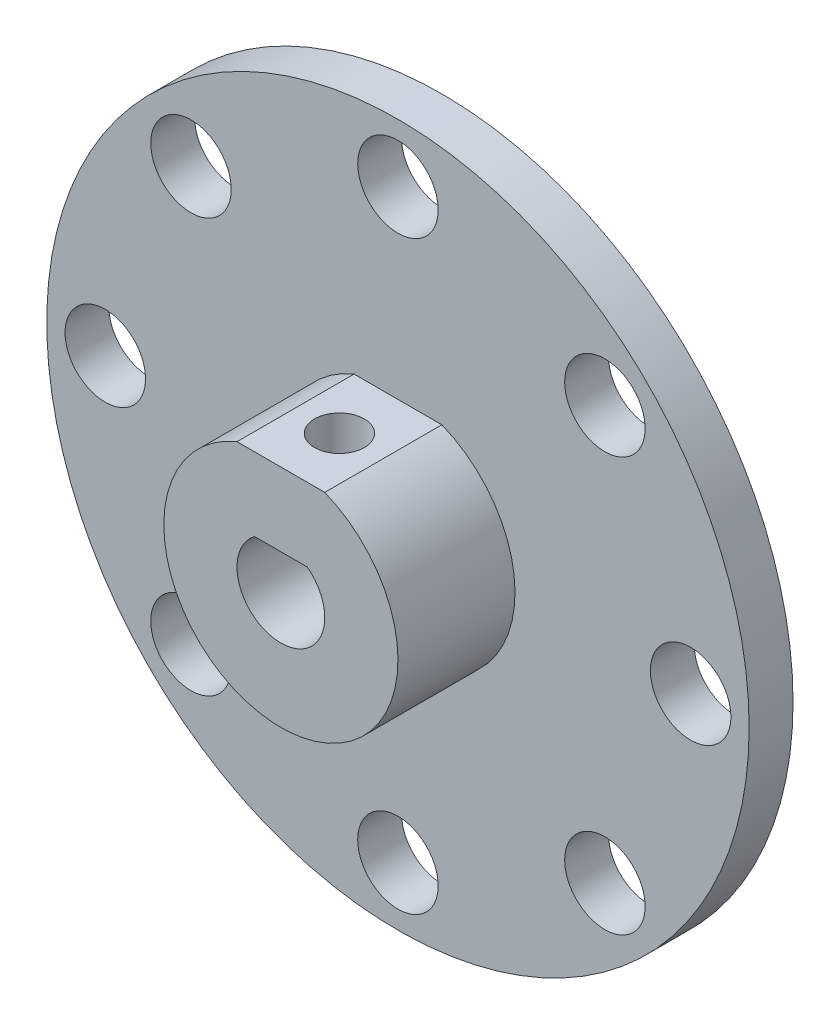
SolidWorks part; units mm, degrees
ref_plane "Alzado" through (0, 0, 0) normal (0, 0, 1) x (1, 0, 0)
ref_plane "Planta" through (0, 0, 0) normal (0, 1, 0) x (1, 0, 0)
ref_plane "Vista lateral" through (0, 0, 0) normal (1, 0, 0) x (0, 0, -1)
sketch "Croquis1" plane through (0, 0, 0) normal (1, 0, 0) x (0, 0, -1)
  line L0 (0, 16.8101) -> (0, -16.8101) construction
  line L1 (-25.6232, 0) -> (25.6232, 0) construction
  line L2 (-6.5, 0) -> (6.5, 0)
  line L3 (6.5, 0) -> (6.5, 9)
  line L4 (6.5, 9) -> (4.5, 9)
  line L5 (4.5, 9) -> (4.5, 24)
  line L6 (4.5, 24) -> (1.5, 24)
  line L7 (1.5, 24) -> (1.5, 8)
  line L8 (1.5, 8) -> (-6.5, 8)
  line L9 (-6.5, 8) -> (-6.5, 0)
  point P5 (0, 0)
  point P8 (0, 0)
  dimension "D1" = 9
  dimension "D2" = 24
  dimension "D3" = 2
  dimension "D4" = 13
  dimension "D5" = 3
  dimension "D6" = 8
revolve "Revolución1" add sketch "Croquis1" angle 360 about L1
sketch "Croquis2" plane through (0, 0, 6.5) normal (0, 0, 1) x (1, 0, 0)
  line L0 (-1.8, 2.4) -> (1.8, 2.4)
  arc A0 (-1.8, 2.4) -> (1.8, 2.4) centre (0, 0) ccw
  dimension "D1" = 6
  dimension "D2" = 5.4
extrude "Cortar-Extruir1" cut sketch "Croquis2" against normal blind 10
sketch "Croquis3" plane through (0, 0, -4.5) normal (0, 0, -1) x (-1, 0, 0)
  circle A0 centre (0, 0) radius 20 construction
  point P3 (0, 20)
  point P4 (0, 0)
  point P5 (0, 0)
  point P7 (14.1421, 14.1421)
  point P8 (20, 0)
  point P9 (14.1421, -14.1421)
  point P10 (0, -20)
  point P11 (-14.1421, -14.1421)
  point P12 (-20, 0)
  point P13 (-14.1421, 14.1421)
  point P14 (0, 0)
  dimension "D1" = 40
  dimension "D2" = 8
hole_wizard "Taladro de margen para M51" positions "Croquis3D4" profile "Croquis9" hole size "M5" standard "Ansi Metric" end condition up to next
sketch3d "Croquis3D4"
  point P0 (0, 20, -4.5)
  point P3 (-14.1421, 14.1421, -4.5)
  point P6 (-20, 0, -4.5)
  point P9 (-14.1421, -14.1421, -4.5)
  point P12 (0, -20, -4.5)
  point P15 (14.1421, -14.1421, -4.5)
  point P18 (20, 0, -4.5)
  point P21 (14.1421, 14.1421, -4.5)
sketch "Croquis9" plane through (0, 20, -4.5) normal (1, 0, 0) x (0, 1, 0)
  line L0 (0, 0) -> (0, 3)
  line L1 (0, 3) -> (2.75, 3)
  line L2 (2.75, 3) -> (2.75, 0)
  line L5 (2.75, 0) -> (0, 0)
  line L11 (0, -6.35) -> (0, 107.95) construction
  dimension "Diámetro de taladro hasta el siguiente" = 5.5
  dimension "Profundidad de taladro hasta el siguiente" = 3
sketch "Croquis10" plane through (0, 0, 6.5) normal (0, 0, 1) x (1, 0, 0)
  line L0 (-3, 7.4162) -> (3, 7.4162)
  circle A0 centre (0, 0) radius 8 construction
  arc A1 (3, 7.4162) -> (-3, 7.4162) centre (0, 0) ccw
  dimension "D1" = 6
extrude "Cortar-Extruir2" cut sketch "Croquis10" against normal up to surface (8 mm away) up to face at (-2.75, 20, -1.5)
sketch "Croquis11" plane through (0, 7.4162, 0) normal (0, 1, 0) x (1, 0, 0)
  line L4 (-3, 1.5) -> (-3, -6.5)
  line L5 (-3, -6.5) -> (3, -6.5)
  line L6 (3, -6.5) -> (3, 1.5)
  line L7 (3, 1.5) -> (-3, 1.5)
  line L8 (-3, 1.5) -> (-3, -6.5)
  line L9 (-3, -6.5) -> (3, -6.5)
  line L10 (3, -6.5) -> (3, 1.5)
  line L11 (3, 1.5) -> (-3, 1.5)
  point P2 (0, -2.5)
  point P6 (-3, -2.5)
  point P8 (0, -6.5)
  dimension "D1" = 0
hole_wizard "Taladro de margen para M31" positions "Croquis3D5" profile "Croquis12" hole size "M3" standard "Ansi Metric"
sketch3d "Croquis3D5"
  point P0 (0, 7.4162, 2.5)
sketch "Croquis12" plane through (0, 7.4162, 2.5) normal (1, 0, 0) x (0, 0, 1)
  line L0 (0, 0) -> (0, 5.0162)
  line L1 (0, 5.0162) -> (1.7, 5.0162)
  line L2 (1.7, 5.0162) -> (1.7, 0)
  line L5 (1.7, 0) -> (0, 0)
  line L11 (0, -6.35) -> (0, 107.95) construction
  dimension "Diámetro de taladro hasta el siguiente" = 3.4
  dimension "Profundidad de taladro hasta el siguiente" = 5.0162
